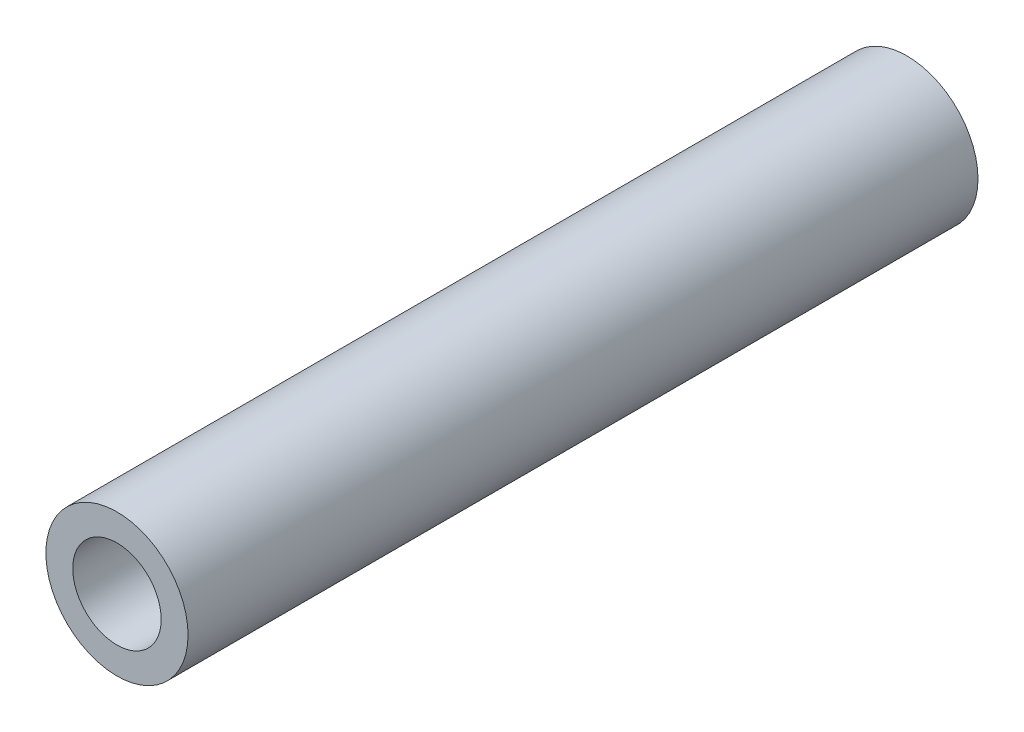
SolidWorks part; units mm, degrees
ref_plane "Alzado" through (0, 0, 0) normal (0, 0, 1) x (1, 0, 0)
ref_plane "Planta" through (0, 0, 0) normal (0, 1, 0) x (1, 0, 0)
ref_plane "Vista lateral" through (0, 0, 0) normal (1, 0, 0) x (0, 0, -1)
sketch "Croquis1" plane through (0, 0, 0) normal (0, 0, 1) x (1, 0, 0)
  circle A0 centre (0, 0) radius 1.12
  circle A1 centre (0, 0) radius 1.8
  dimension "D1" = 2.24
  dimension "D2" = 3.6
extrude "Saliente-Extruir1" add sketch "Croquis1" along normal blind 20
sketch "Croquis2" plane through (0, 0, 20) normal (0, 0, 1) x (1, 0, 0)
  line L0 (-1.12, 0) -> (1.12, 0) construction
  line L1 (0, -1.12) -> (0, 1.12) construction
  circle A0 centre (0, 0) radius 1.12 construction
  point P8 (0, 0)
  point P13 (0, 0)
